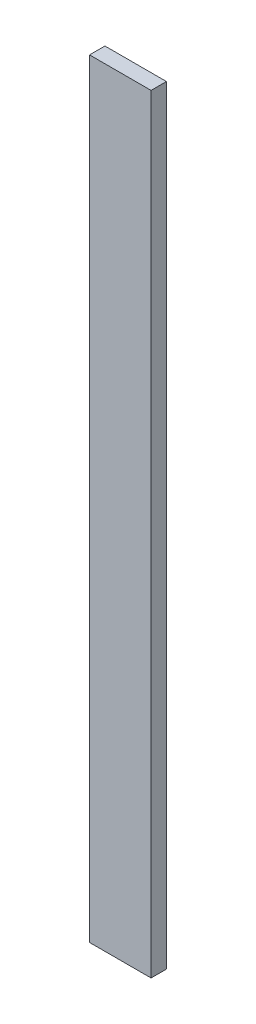
SolidWorks part; units mm, degrees
ref_plane "Front Plane" through (0, 0, 0) normal (0, 0, 1) x (1, 0, 0)
ref_plane "Top Plane" through (0, 0, 0) normal (0, 1, 0) x (1, 0, 0)
ref_plane "Right Plane" through (0, 0, 0) normal (1, 0, 0) x (0, 0, -1)
sketch "Sketch1" plane through (0, 0, 0) normal (0, 0, 1) x (1, 0, 0)
  line L1 (-10, -125) -> (10, -125)
  line L2 (-10, -125) -> (-10, 125)
  line L3 (-10, 125) -> (10, 125)
  line L4 (10, -125) -> (10, 125)
  line L5 (-10, -125) -> (10, 125) construction
  line L6 (-10, 125) -> (10, -125) construction
  point P0 (0, 0)
  dimension "D1" = 250
  dimension "D2" = 20
extrude "Boss-Extrude1" add sketch "Sketch1" along normal blind 5
